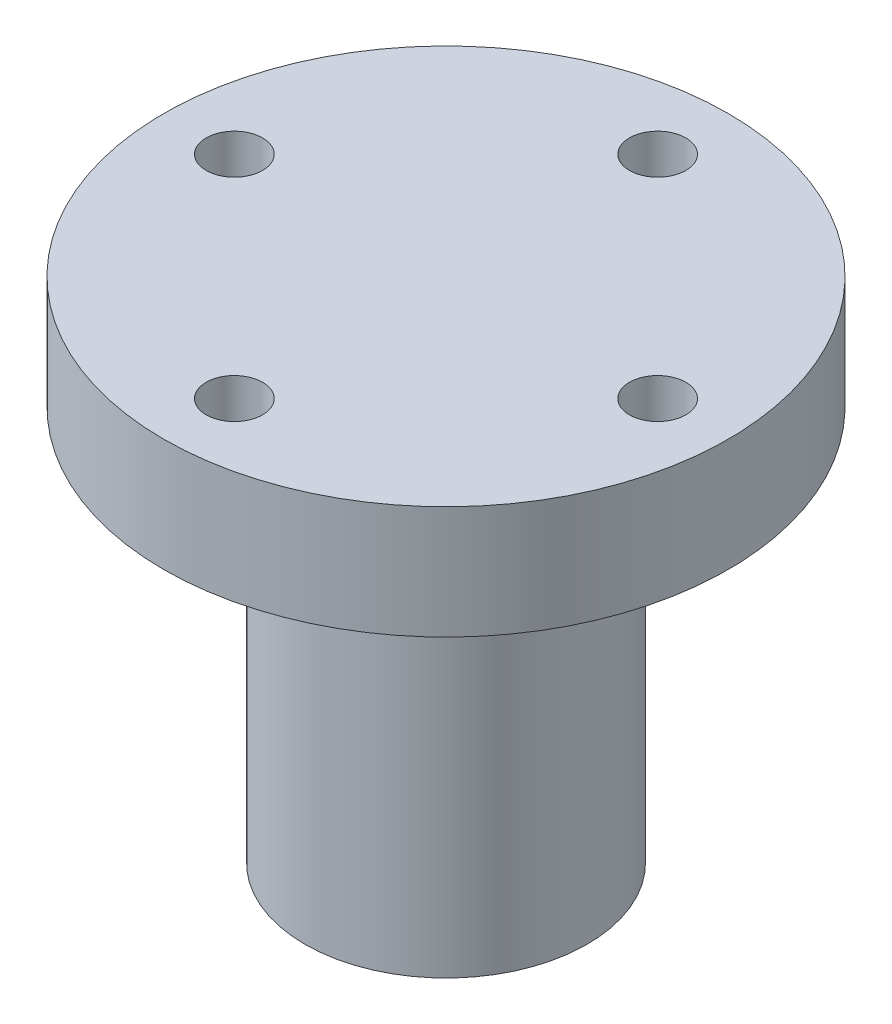
SolidWorks part; units mm, degrees
ref_plane "Front" through (0, 0, 0) normal (0, 0, 1) x (1, 0, 0)
ref_plane "Top" through (0, 0, 0) normal (0, 1, 0) x (1, 0, 0)
ref_plane "Right" through (0, 0, 0) normal (1, 0, 0) x (0, 0, -1)
sketch "Croquis1" plane through (0, 0, 0) normal (0, 1, 0) x (1, 0, 0)
  circle A0 centre (0, 0) radius 25
  dimension "D1" = 50
extrude "Saliente-Extruir1" add sketch "Croquis1" along normal mid plane 70
sketch "Croquis2" plane through (0, 35, 0) normal (0, 1, 0) x (1, 0, 0)
  circle A0 centre (0, 0) radius 50
  dimension "D1" = 100
extrude "Saliente-Extruir2" add sketch "Croquis2" along normal blind 20
sketch "Croquis3" plane through (0, 55, 0) normal (0, 1, 0) x (1, 0, 0)
  line L0 (0, -50) -> (0, 50) construction
  circle A2 centre (0, 37.5) radius 5
  circle A3 centre (37.5, 0) radius 5
  circle A4 centre (0, -37.5) radius 5
  circle A5 centre (-37.5, 0) radius 5
  dimension "D1" = 37.5
  dimension "D2" = 10
  dimension "D3" = 4
extrude "Cortar-Extruir1" cut sketch "Croquis3" against normal up to next
